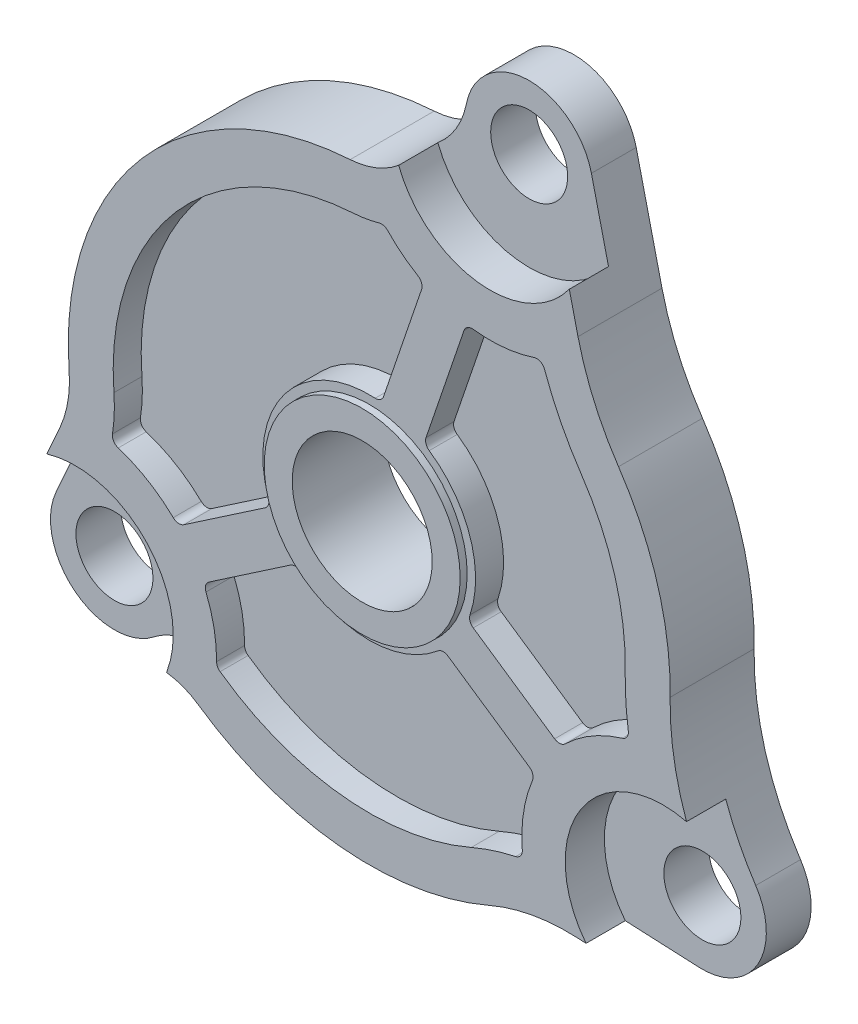
SolidWorks part; units mm, degrees
ref_plane "Plane1" through (0, 0, 0) normal (0, 0, 1) x (1, 0, 0)
ref_plane "Plane2" through (0, 0, 0) normal (0, 1, 0) x (-1, 0, 0)
ref_plane "Plane3" through (0, 0, 0) normal (1, 0, 0) x (0, 0, -1)
sketch "Sketch1" plane through (0, 0, 0) normal (0, 0, 1) x (1, 0, 0)
  line L0 (-26.67, -18.1463) -> (26.67, -18.1463) construction
  line L1 (0, 0) -> (-26.67, -18.1463) construction
  line L2 (0, 0) -> (26.67, -18.1463) construction
  line L3 (10.9563, 32.2244) -> (0, 0) construction
  line L4 (16.6043, 33.5606) -> (18.9435, 23.6736)
  line L6 (18.789, -23.5906) -> (26.4008, -23.944)
  line L11 (-28.0689, -6.9945) -> (-31.9746, -15.7912)
  line L12 (-18.0518, -25.6544) -> (0, 0) construction
  arc A0 (-15.5264, -22.4609) -> (-23.0728, -22.7011) centre (-19.1372, -27.6844) ccw
  arc A1 (-31.9746, -15.7912) -> (-23.0728, -22.7011) centre (-26.67, -18.1463) ccw
  arc A3 (16.6043, 33.5606) -> (5.2649, 33.3618) centre (10.9563, 32.2244) ccw
  arc A4 (27.3007, -0.4835) -> (22.6196, 15.2943) centre (0, 0) ccw
  arc A5 (31.511, -14.9447) -> (27.3007, -0.4835) centre (52.6967, -0.9332) cw
  arc A6 (5.2649, 33.3618) -> (-1.7257, 27.2504) centre (-2.2073, 34.8552) cw
  arc A7 (-1.7257, 27.2504) -> (-27.2247, -2.0929) centre (0, 0) ccw
  arc A9 (26.4008, -23.944) -> (31.511, -14.9447) centre (26.67, -18.1463) ccw
  arc A10 (-15.5264, -22.4609) -> (10.8798, -25.0438) centre (0, 0) ccw
  arc A12 (-27.2247, -2.0929) -> (-28.0689, -6.9945) centre (-37.3548, -2.8716) cw
  arc A13 (22.6196, 15.2943) -> (18.9435, 23.6736) centre (43.6611, 29.5216) cw
  arc A14 (18.789, -23.5906) -> (10.8798, -25.0438) centre (17.9643, -41.3514) ccw
  circle A18 centre (10.9563, 32.2244) radius 3.4925
  circle A19 centre (-26.67, -18.1463) radius 3.4925
  circle A20 centre (26.67, -18.1463) radius 3.4925
  dimension "D1" = 54.61
  dimension "D2" = 53.34
  dimension "D3" = 11.6078
  dimension "D4" = 32.258
  dimension "D7" = 6.35
  dimension "D8" = 10.16
  dimension "D9" = 7.62
  dimension "D10" = 25.4
  dimension "D11" = 17.78
  dimension "D20" = 6.985
  dimension "D5" = 34.036
  dimension "D6" = 105.453
  dimension "D12" = 10.16
  dimension "D13" = 7.62
  dimension "D17" = 31.369
  dimension "D18" = 11.43
  dimension "D19" = 9.6247
extrude "Base" add sketch "Sketch1" along normal blind 7.62
ref_plane "Plane5" through (0, 0, 8.255) normal (0, 0, 1) x (1, 0, 0)
sketch "Sketch2" plane through (0, 0, 8.255) normal (0, 0, 1) x (1, 0, 0)
  circle A0 centre (0, 0) radius 8.89
  dimension "D1" = 17.78
extrude "Boss-Extrude1" add sketch "Sketch2" against normal up to surface (0.635 mm away)
sketch "Sketch3" plane through (0, 0, 7.62) normal (0, 0, 1) x (1, 0, 0)
  line L0 (-16.8205, -8.987) -> (-9.4374, -3.9635)
  line L1 (8.6002, 18.9822) -> (5.1532, 8.8441)
  line L2 (4.7525, 20.2904) -> (1.3055, 10.1523)
  line L3 (7.1513, -7.3235) -> (14.5343, -12.347)
  line L4 (-14.5343, -12.347) -> (-7.1513, -7.3235)
  line L5 (9.4374, -3.9635) -> (16.8205, -8.987)
  arc A0 (-1.4681, 23.1825) -> (-23.1606, -1.7805) centre (0, 0) ccw
  arc A1 (-9.4374, -3.9635) -> (-9.1442, -3.0896) centre (-9.8661, -3.3335) ccw
  arc A2 (9.1442, -3.0896) -> (5.4448, 7.9696) centre (0, 0) ccw
  arc A3 (5.1532, 8.8441) -> (5.4448, 7.9696) centre (5.8747, 8.5988) ccw
  arc A4 (0.5414, 9.6368) -> (1.3055, 10.1523) centre (0.5841, 10.3976) ccw
  arc A5 (-13.5281, -18.8831) -> (9.2557, -21.3053) centre (0, 0) ccw
  arc A6 (13.2921, -20.0006) -> (9.2557, -21.3053) centre (17.9643, -41.3514) ccw
  arc A7 (13.2921, -20.0006) -> (13.8887, -19.1939) centre (13.1292, -19.2562) ccw
  arc A8 (14.8104, -13.2669) -> (13.8887, -19.1939) centre (26.67, -18.1463) ccw
  arc A9 (14.8104, -13.2669) -> (14.5343, -12.347) centre (14.1057, -12.977) ccw
  arc A10 (7.1513, -7.3235) -> (6.2307, -7.3715) centre (6.7226, -7.9535) ccw
  arc A11 (-6.2307, -7.3715) -> (-7.1513, -7.3235) centre (-6.7226, -7.9535) ccw
  arc A12 (-13.8463, -18.2571) -> (-14.8104, -13.2669) centre (-26.67, -18.1463) ccw
  arc A13 (-14.5343, -12.347) -> (-14.8104, -13.2669) centre (-14.1057, -12.977) ccw
  arc A14 (-13.8463, -18.2571) -> (-13.5281, -18.8831) centre (-13.0843, -18.2637) ccw
  arc A15 (-17.7775, -8.906) -> (-16.8205, -8.987) centre (-17.2492, -8.357) ccw
  arc A16 (-17.7775, -8.906) -> (-22.7707, -5.9293) centre (-26.67, -18.1463) ccw
  arc A17 (22.972, -5.8669) -> (17.7775, -8.906) centre (26.67, -18.1463) ccw
  arc A18 (22.972, -5.8669) -> (23.5069, -5.0313) centre (22.7523, -5.1373) ccw
  arc A19 (23.2253, -0.4113) -> (23.5069, -5.0313) centre (52.6967, -0.9332) ccw
  arc A20 (23.2253, -0.4113) -> (19.2429, 13.0112) centre (0, 0) ccw
  arc A21 (15.9142, 19.5741) -> (19.2429, 13.0112) centre (43.6611, 29.5216) ccw
  arc A22 (9.4133, 19.4933) -> (8.6002, 18.9822) centre (9.3216, 18.7369) ccw
  arc A23 (9.4133, 19.4933) -> (14.9591, 20.0409) centre (10.9563, 32.2244) ccw
  arc A24 (16.8205, -8.987) -> (17.7775, -8.906) centre (17.2492, -8.357) ccw
  arc A25 (9.1442, -3.0896) -> (9.4374, -3.9635) centre (9.8661, -3.3335) ccw
  arc A26 (15.9142, 19.5741) -> (14.9591, 20.0409) centre (15.1969, 19.317) ccw
  arc A27 (-1.4681, 23.1825) -> (0.9185, 23.5845) centre (-2.2073, 34.8552) ccw
  arc A28 (4.7525, 20.2904) -> (4.4195, 21.1912) centre (4.0311, 20.5357) ccw
  arc A29 (1.6737, 23.376) -> (4.4195, 21.1912) centre (10.9563, 32.2244) ccw
  arc A30 (1.6737, 23.376) -> (0.9185, 23.5845) centre (1.1222, 22.8502) ccw
  arc A31 (-23.2918, -5.0849) -> (-23.1606, -1.7805) centre (-37.3548, -2.8716) ccw
  arc A32 (-23.2918, -5.0849) -> (-22.7707, -5.9293) centre (-22.5391, -5.2034) ccw
  arc A33 (-6.2307, -7.3715) -> (6.2307, -7.3715) centre (0, 0) ccw
  arc A34 (0.5414, 9.6368) -> (-9.1442, -3.0896) centre (0, 0) ccw
extrude "Ribs" cut sketch "Sketch3" against normal blind 2.54
sketch "Sketch4" plane through (0, 0, 7.62) normal (0, 0, 1) x (1, 0, 0)
  line L0 (18.1547, 27.0075) -> (18.1547, 40.0401)
  line L1 (2.6711, 29.0015) -> (2.6711, 40.0401)
  line L2 (2.6711, 40.0401) -> (18.1547, 40.0401)
  arc A3 (2.6711, 29.0015) -> (18.1547, 27.0075) centre (10.9563, 32.2244) ccw
extrude "Ear 1" cut sketch "Sketch4" against normal blind 3.556
sketch "Sketch5" plane through (0, 0, 7.62) normal (0, 0, 1) x (1, 0, 0)
  line L0 (37.5407, -9.5127) -> (37.5407, -27.8508)
  line L1 (37.5407, -27.8508) -> (19.674, -27.8508)
  line L2 (37.5407, -9.5127) -> (28.7896, -9.5127)
  line L3 (19.674, -23.6317) -> (19.674, -27.8508)
  arc A0 (28.7896, -9.5127) -> (19.674, -23.6317) centre (26.67, -18.1463) ccw
extrude "Ear 2" cut sketch "Sketch5" against normal blind 3.556
sketch "Sketch6" plane through (0, 0, 7.62) normal (0, 0, 1) x (1, 0, 0)
  line L0 (-29.2419, -9.6365) -> (-37.3548, -9.6365)
  line L1 (-20.6172, -25.6556) -> (-20.6172, -30.1962)
  line L2 (-20.6172, -30.1962) -> (-37.3548, -30.1962)
  line L3 (-37.3548, -30.1962) -> (-37.3548, -9.6365)
  arc A0 (-20.001, -24.0249) -> (-29.2419, -9.6365) centre (-26.67, -18.1463) ccw
  arc A1 (-20.001, -24.0249) -> (-20.6172, -25.6556) centre (-18.1511, -25.6556) ccw
extrude "Ear 3" cut sketch "Sketch6" against normal blind 3.556
sketch "Sketch7" plane through (0, 0, 8.255) normal (0, 0, 1) x (1, 0, 0)
  circle A0 centre (0, 0) radius 6.35
  dimension "D1" = 12.7
extrude "Cut-Extrude5" cut sketch "Sketch7" against normal through all
